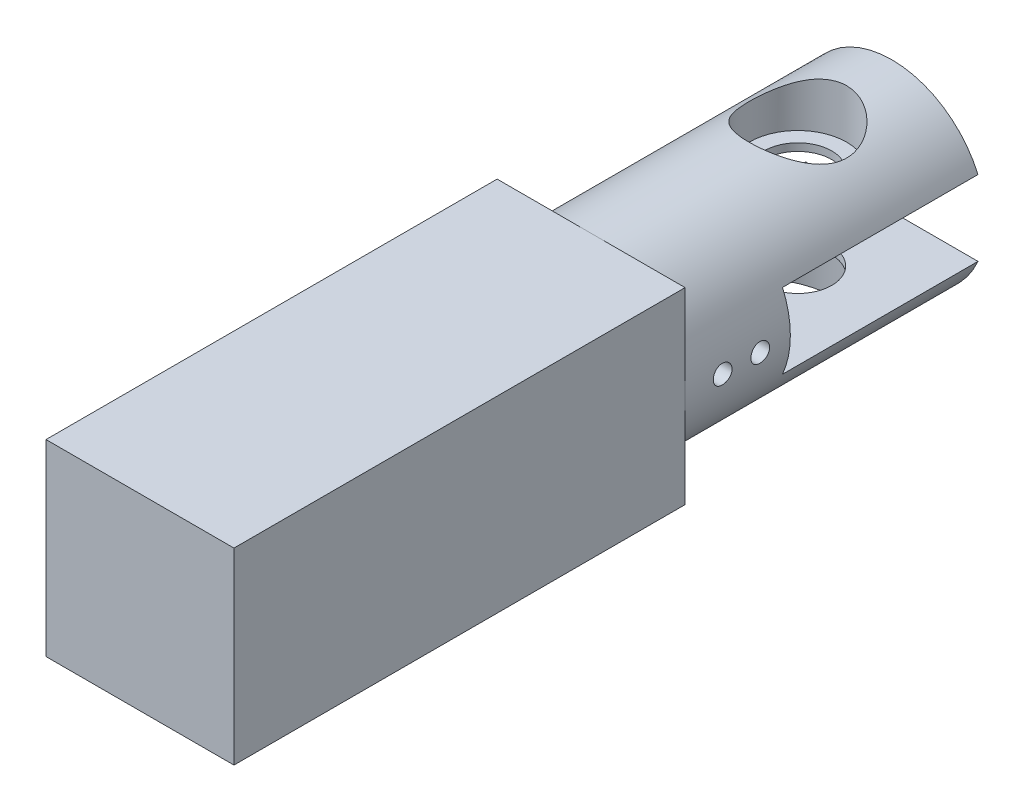
SolidWorks part; units mm, degrees
ref_plane "정면" through (0, 0, 0) normal (0, 0, 1) x (1, 0, 0)
ref_plane "윗면" through (0, 0, 0) normal (0, 1, 0) x (1, 0, 0)
ref_plane "우측면" through (0, 0, 0) normal (1, 0, 0) x (0, 0, -1)
sketch "스케치1" plane through (0, 0, 0) normal (0, 0, 1) x (1, 0, 0)
  circle A0 centre (0, 0) radius 12.5
  dimension "D1" = 25
extrude "보스-돌출1" add sketch "스케치1" against normal blind 100 contours A0
sketch "스케치2" plane through (0, 0, -100) normal (0, 0, -1) x (-1, 0, 0)
  line L0 (18.4039, 0) -> (-28.4221, 0) construction
  line L2 (11.4564, 5) -> (-11.4564, 5)
  line L4 (11.4564, -5) -> (-11.4564, -5)
  circle A1 centre (0, 0) radius 12.5 construction
  arc A5 (11.4564, -5) -> (11.4564, 5) centre (0, 0) ccw
  circle A6 centre (0, 0) radius 12.5
  arc A7 (-11.4564, 5) -> (-11.4564, -5) centre (0, 0) ccw
  dimension "D2" = 5
  dimension "D1" = 0
extrude "컷-돌출1" cut sketch "스케치2" against normal blind 26
ref_plane "평면2" through (12.5, 0, 0) normal (1, 0, 0) x (0, 0, -1)
sketch "스케치3" plane through (0, 0, 0) normal (0, 1, 0) x (1, 0, 0)
  line L0 (25.0967, 87.5) -> (-34.827, 87.5) construction
  line L2 (12.5, 0) -> (12.5, 74) construction
  line L3 (12.5, -11.7673) -> (12.5, 74) construction
  line L6 (12.5, 74) -> (11.4564, 74) construction
  circle A0 centre (0, 87.5) radius 4.5
  dimension "D1" = 9
  dimension "D2" = 13.5
extrude "컷-돌출2" cut sketch "스케치3" against normal blind 36.5348 and the other way blind 34
ref_plane "평면3" through (0, 6, 0) normal (0, -1, 0) x (-1, 0, 0)
sketch "스케치6" plane through (0, 6, 0) normal (0, 1, 0) x (1, 0, 0)
  circle A0 centre (0, 87.5) radius 6.5
  dimension "D1" = 13
extrude "컷-돌출5" cut sketch "스케치6" along normal blind 16
mirror "대칭 복사1" about plane through (0, 0, 0) normal (0, 1, 0) of "컷-돌출5"
sketch "스케치7" plane through (0, 0, -74) normal (0, 0, -1) x (-1, 0, 0)
  line L5 (-9, -2.5) -> (9, -2.5)
  line L6 (-9, -2.5) -> (-9, 2.5)
  line L7 (-9, 2.5) -> (9, 2.5)
  line L8 (9, -2.5) -> (9, 2.5)
  line L9 (-9, -2.5) -> (9, 2.5) construction
  line L10 (-9, 2.5) -> (9, -2.5) construction
  point P0 (0, 0)
  point P6 (9, 0.944)
  dimension "D1" = 5
  dimension "D2" = 18
extrude "컷-돌출6" cut sketch "스케치7" against normal blind 13
sketch "스케치9" plane through (12.5, 0, 0) normal (1, 0, 0) x (0, 0, -1)
  line L0 (74, -5) -> (74, 5) construction
  line L2 (61, 2.5) -> (61, -2.5) construction
  circle A0 centre (70, 0) radius 1.25
  circle A1 centre (65, 0) radius 1.25
  dimension "D1" = 2.5
  dimension "D2" = 4
  dimension "D3" = 4
extrude "컷-돌출7" cut sketch "스케치9" against normal blind 44
sketch "스케치10" plane through (0, 0, 0) normal (0, 0, 1) x (1, 0, 0)
  line L1 (-12.5, -12.5) -> (12.5, -12.5)
  line L2 (-12.5, -12.5) -> (-12.5, 12.5)
  line L3 (-12.5, 12.5) -> (12.5, 12.5)
  line L4 (12.5, -12.5) -> (12.5, 12.5)
  line L5 (-12.5, -12.5) -> (12.5, 12.5) construction
  line L6 (-12.5, 12.5) -> (12.5, -12.5) construction
  point P0 (0, 0)
extrude "보스-돌출2" add sketch "스케치10" against normal blind 60
